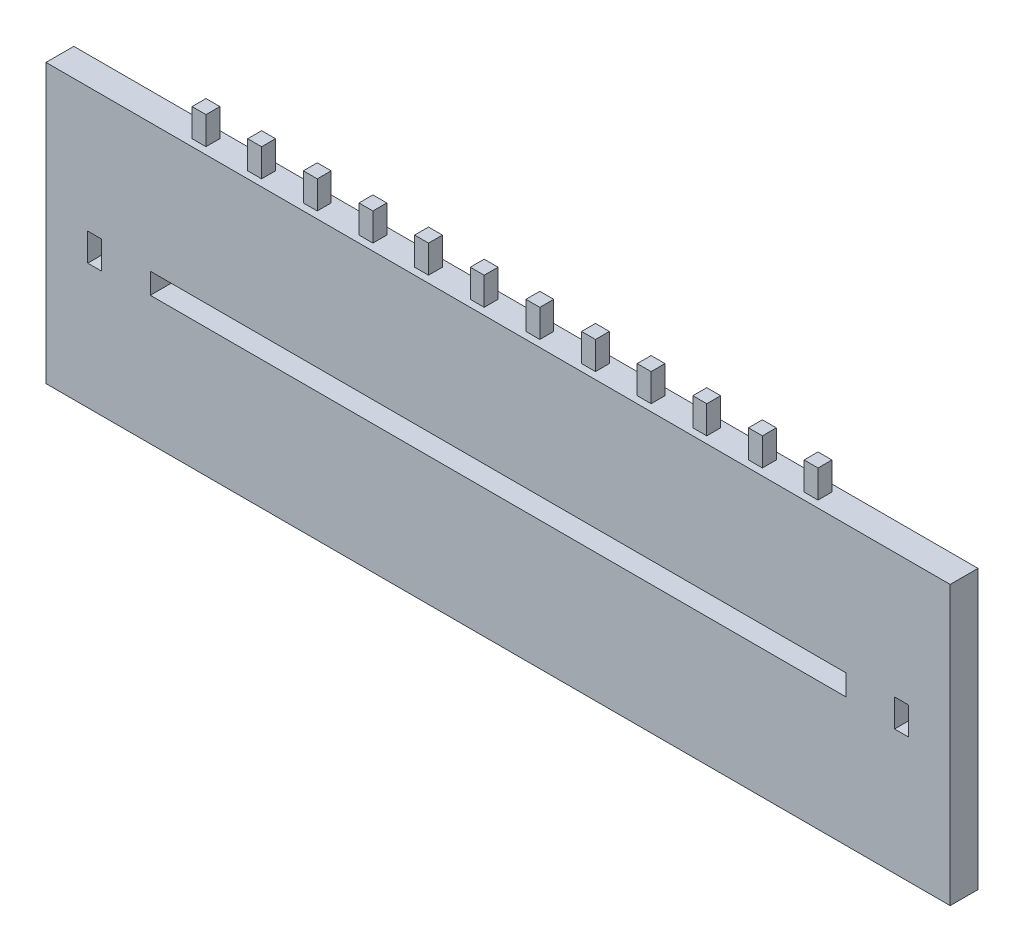
SolidWorks part; units mm, degrees
ref_plane "Front Plane" through (0, 0, 0) normal (0, 0, 1) x (1, 0, 0)
ref_plane "Top Plane" through (0, 0, 0) normal (0, 1, 0) x (1, 0, 0)
ref_plane "Right Plane" through (0, 0, 0) normal (1, 0, 0) x (0, 0, -1)
sketch "Sketch1" plane through (0, 0, 0) normal (0, 0, 1) x (1, 0, 0)
  line L0 (290, 100) -> (290, -100) construction
  line L1 (-325, 100) -> (325, 100)
  line L2 (-325, 100) -> (-325, -100)
  line L3 (-325, -100) -> (325, -100)
  line L4 (325, 100) -> (325, -100)
  line L5 (0, 100) -> (0, -100) construction
  line L6 (-290, 100) -> (-290, -100) construction
  line L7 (250, 0) -> (-250, 0) construction
  line L8 (-250, 7.5) -> (250, 7.5)
  line L9 (-250, 7.5) -> (-250, -7.5)
  line L10 (-250, -7.5) -> (250, -7.5)
  line L11 (250, 7.5) -> (250, -7.5)
  line L13 (-295, 10) -> (-285, 10)
  line L14 (-295, 10) -> (-295, -10)
  line L15 (-295, -10) -> (-285, -10)
  line L16 (-285, 10) -> (-285, -10)
  line L17 (285, 10) -> (295, 10)
  line L18 (285, 10) -> (285, -10)
  line L19 (285, -10) -> (295, -10)
  line L20 (295, 10) -> (295, -10)
  point P15 (0, 0)
  point P21 (0, 7.5)
  point P24 (-290, 10)
  point P31 (290, 10)
  dimension "D3" = 20
  dimension "D1" = 650
  dimension "D2" = 200
  dimension "D4" = 10
  dimension "D5" = 500
  dimension "D6" = 15
  dimension "D7" = 35
  dimension "D8" = 90
  dimension "D9" = 10
  dimension "D10" = 20
  dimension "D11" = 90
extrude "Boss-Extrude1" add sketch "Sketch1" along normal blind 20
sketch "Sketch2" plane through (0, 100, 0) normal (0, 1, 0) x (1, 0, 0)
  line L1 (325, 0) -> (-325, 0) construction
  line L2 (-325, -20) -> (-325, 0) construction
  line L3 (325, -20) -> (-325, -20) construction
  line L4 (-185, -5) -> (-185, -15)
  line L5 (325, 0) -> (-325, 0) construction
  line L6 (-325, -20) -> (-325, 0) construction
  line L7 (325, -20) -> (-325, -20) construction
  line L8 (-325, -10) -> (325, -10) construction
  line L9 (-185, -5) -> (-175, -5)
  line L11 (-225, -5) -> (-215, -5)
  line L12 (-225, -5) -> (-225, -15)
  line L13 (-225, -15) -> (-215, -15)
  line L14 (-215, -5) -> (-215, -15)
  line L15 (-225, -5) -> (-215, -15) construction
  line L16 (-225, -15) -> (-215, -5) construction
  line L17 (-175, -5) -> (-175, -15)
  line L18 (-185, -15) -> (-175, -15)
  line L19 (-145, -5) -> (-145, -15)
  line L20 (-145, -5) -> (-135, -5)
  line L21 (-135, -5) -> (-135, -15)
  line L22 (-145, -15) -> (-135, -15)
  line L23 (-105, -5) -> (-105, -15)
  line L24 (-105, -5) -> (-95, -5)
  line L25 (-95, -5) -> (-95, -15)
  line L26 (-105, -15) -> (-95, -15)
  line L27 (-65, -5) -> (-65, -15)
  line L28 (-65, -5) -> (-55, -5)
  line L29 (-55, -5) -> (-55, -15)
  line L30 (-65, -15) -> (-55, -15)
  line L31 (-25, -5) -> (-25, -15)
  line L32 (-25, -5) -> (-15, -5)
  line L33 (-15, -5) -> (-15, -15)
  line L34 (-25, -15) -> (-15, -15)
  line L35 (15, -5) -> (15, -15)
  line L36 (15, -5) -> (25, -5)
  line L37 (25, -5) -> (25, -15)
  line L38 (15, -15) -> (25, -15)
  line L39 (55, -5) -> (55, -15)
  line L40 (55, -5) -> (65, -5)
  line L41 (65, -5) -> (65, -15)
  line L42 (55, -15) -> (65, -15)
  line L43 (95, -5) -> (95, -15)
  line L44 (95, -5) -> (105, -5)
  line L45 (105, -5) -> (105, -15)
  line L46 (95, -15) -> (105, -15)
  line L47 (135, -5) -> (135, -15)
  line L48 (135, -5) -> (145, -5)
  line L49 (145, -5) -> (145, -15)
  line L50 (135, -15) -> (145, -15)
  line L51 (175, -5) -> (175, -15)
  line L52 (175, -5) -> (185, -5)
  line L53 (185, -5) -> (185, -15)
  line L54 (175, -15) -> (185, -15)
  line L55 (215, -5) -> (215, -15)
  line L56 (215, -5) -> (225, -5)
  line L57 (225, -5) -> (225, -15)
  line L58 (215, -15) -> (225, -15)
  point P9 (-220, -10)
  dimension "D1" = 105
  dimension "D4" = 12
  dimension "D2" = 10
  dimension "D3" = 10
extrude "Boss-Extrude2" add sketch "Sketch2" along normal blind 20
